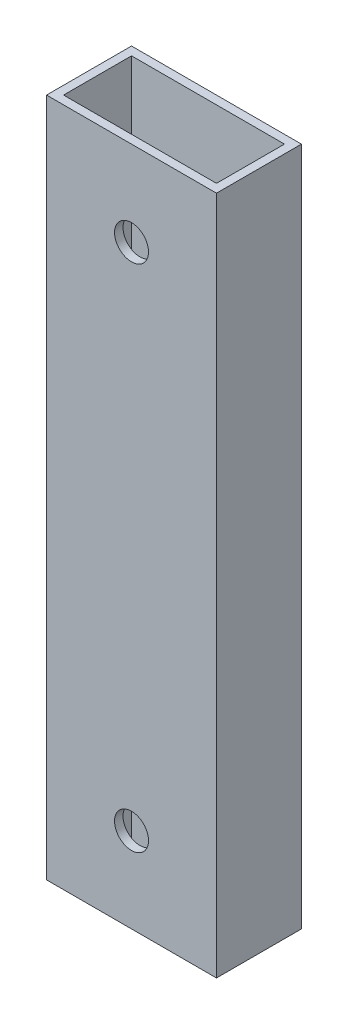
SolidWorks part; units mm, degrees
ref_plane "前视基准面" through (0, 0, 0) normal (0, 0, 1) x (1, 0, 0)
ref_plane "上视基准面" through (0, 0, 0) normal (0, 1, 0) x (1, 0, 0)
ref_plane "右视基准面" through (0, 0, 0) normal (1, 0, 0) x (0, 0, -1)
sketch "草图1" plane through (0, 0, 0) normal (0, 1, 0) x (1, 0, 0)
  line L0 (-9, 4) -> (-9, -4)
  line L1 (-10, 5) -> (10, 5)
  line L2 (-10, 5) -> (-10, -5)
  line L3 (-10, -5) -> (10, -5)
  line L4 (10, 5) -> (10, -5)
  line L5 (-10, 5) -> (10, -5) construction
  line L6 (-10, -5) -> (10, 5) construction
  line L7 (-9, -4) -> (9, -4)
  line L8 (9, 4) -> (9, -4)
  line L9 (-9, 4) -> (9, 4)
  point P0 (0, 0)
  dimension "D1" = 1
extrude "凸台-拉伸1" add sketch "草图1" along normal blind 80
hole_wizard "Ø4.0 (4) 直径孔1" positions "草图3" profile "草图2" hole size "Ø4.0" standard "GB" end condition through all
sketch "草图3" plane through (0, 0, -5) normal (0, 0, -1) x (-1, 0, 0)
  line L0 (0, 10) -> (0, 0)
  line L1 (-10, 0) -> (10, 0) construction
  line L3 (0, 70) -> (0, 80)
  line L4 (-10, 80) -> (10, 80) construction
  point P0 (0, 10)
  point P2 (0, 70)
sketch "草图2" plane through (0, 10, -5) normal (1, 0, 0) x (0, 1, 0)
  line L0 (0, 0) -> (0, 10)
  line L1 (0, 10) -> (2, 10)
  line L2 (2, 10) -> (2, 0)
  line L5 (2, 0) -> (0, 0)
  line L11 (0, -6.35) -> (0, 107.95) construction
  dimension "通孔孔直径" = 4
  dimension "通孔孔深度" = 10
